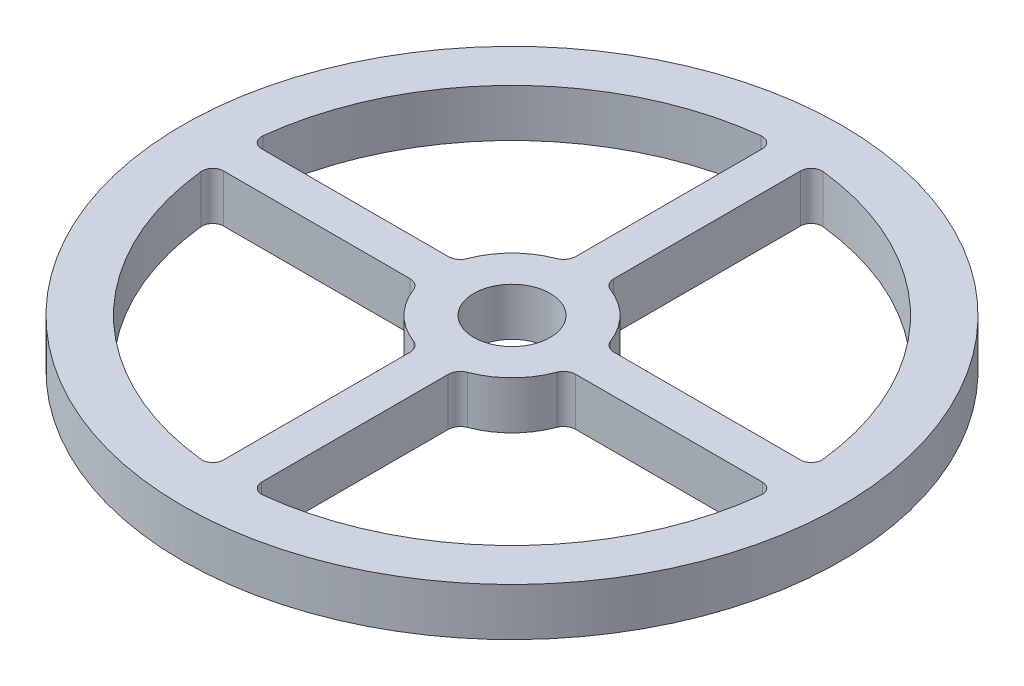
SolidWorks part; units mm, degrees
other "Markup1"
sketch "Sketch3" plane through (-32, 5, -32) normal (0, 1, 0) x (1, 0, 0)
sketch "Sketch4" plane through (-32, 5, -32) normal (0, 1, 0) x (1, 0, 0)
sketch "Sketch5" plane through (-32, 5, -32) normal (0, 1, 0) x (1, 0, 0)
sketch "Sketch6" plane through (-32, 5, -32) normal (0, 1, 0) x (1, 0, 0)
sketch "Sketch9" plane through (-34.5, 5, -34.5) normal (0, 1, 0) x (1, 0, 0)
ref_plane "Front Plane" through (0, 0, 0) normal (0, 0, 1) x (1, 0, 0)
ref_plane "Top Plane" through (0, 0, 0) normal (0, 1, 0) x (1, 0, 0)
ref_plane "Right Plane" through (0, 0, 0) normal (1, 0, 0) x (0, 0, -1)
sketch "Sketch1" plane through (0, 0, 0) normal (0, 1, 0) x (1, 0, 0)
  circle A0 centre (0, 0) radius 34.5
  circle A1 centre (0, 0) radius 4
  dimension "D1" = 69
  dimension "D2" = 8
extrude "Boss-Extrude1" add sketch "Sketch1" along normal blind 5
sketch "Sketch2" plane through (0, 5, 0) normal (0, 1, 0) x (1, 0, 0)
  line L2 (-4, 0) -> (-31.5, 0) construction
  line L3 (0, -4) -> (0, -31.5) construction
  circle A3 centre (0, 0) radius 34.5 construction
  arc A4 (-34.5, 0) -> (0, -34.5) centre (0, 0) ccw construction
  arc A5 (-4, 0) -> (0, -4) centre (0, 0) ccw construction
  circle A8 centre (0, 0) radius 4 construction
  arc A15 (-31.5, 0) -> (0, -31.5) centre (0, 0) ccw construction
  dimension "D1" = 3
sketch "Sketch8" plane through (0, 5, 0) normal (0, 1, 0) x (1, 0, 0)
  line L0 (-28.2013, -2) -> (-8.6981, -2)
  line L1 (-2, -8.646) -> (-2, -28.2087)
  line L2 (0, -4) -> (0, -31.5) construction
  line L3 (-4, 0) -> (-31.5, 0) construction
  line L4 (-2, -29.4587) -> (-3.1194, -28.2087) construction
  line L5 (-2, -28.2087) -> (-2, -30.1122) construction
  line L6 (-3.2424, -29.3213) -> (-2, -29.4587) construction
  line L7 (-29.4513, -2) -> (-28.2013, -3.126) construction
  line L8 (-28.2013, -2) -> (-32.0792, -2) construction
  line L9 (-2, -7.746) -> (-3.5301, -8.8637) construction
  line L10 (-2, -8.646) -> (-2, -7.668) construction
  line L11 (-2.8574, -7.4723) -> (-2, -7.746) construction
  line L12 (-8.6981, -2) -> (-7.2914, -2) construction
  line L13 (-7.4784, -2.8413) -> (-7.7981, -2) construction
  line L14 (-7.7981, -2) -> (-8.4859, -2.8754) construction
  line L15 (-2.8574, -7.4723) -> (-2.7871, -7.4988)
  arc A0 (-7.4784, -2.8413) -> (-2.7871, -7.4988) centre (0, 0) ccw
  arc A1 (-29.3204, -3.25) -> (-3.2424, -29.3213) centre (0, 0) ccw
  arc A2 (-4, 0) -> (0, -4) centre (0, 0) ccw construction
  arc A3 (-34.5, 0) -> (0, -34.5) centre (0, 0) ccw construction
  arc A4 (-3.2424, -29.3213) -> (-2, -28.2087) centre (-3.1194, -28.2087) ccw
  arc A5 (-28.2013, -2) -> (-29.3204, -3.25) centre (-28.2013, -3.126) ccw
  arc A6 (-2.8574, -7.4723) -> (-2, -8.646) centre (-3.2703, -8.6739) cw
  arc A7 (-8.6981, -2) -> (-7.4784, -2.8413) centre (-8.6981, -3.3047) cw
  point P21 (-2, -29.4587)
  point P22 (-28.2013, -2)
  point P23 (-29.4513, -2)
  point P24 (-30.2666, -1.0524)
  point P25 (-29.3204, -3.25)
  point P29 (-28.2013, -2)
  point P31 (-29.3204, -3.25)
  point P32 (-29.4513, -2)
  point P33 (-2, -8.646)
  point P34 (-2.8574, -7.4723)
  point P40 (-7.4784, -2.8413)
  point P42 (-2, -7.746)
  point P43 (-8.6981, -2)
  point P47 (0, 0)
  point P49 (-7.7981, -2)
  dimension "D3" = 4
  dimension "D4" = 5
  dimension "D9" = 1.1194
  dimension "D10" = 0.9
  dimension "D1" = 2
  dimension "D2" = 2
  dimension "D5" = 1.25
  dimension "D6" = 1.25
  dimension "D7" = 1.25
  dimension "D8" = 1.25
  dimension "D11" = 0.9
  dimension "D12" = 0.9
  dimension "D13" = 0.9
sketch "Sketch11" plane through (0, 5, 0) normal (0, 1, 0) x (1, 0, 0)
  line L0 (-29.0603, 13.1467) -> (-9.557, 13.1467)
  line L1 (-2.859, 6.5008) -> (-2.859, -13.0619)
  arc A0 (-8.3374, 12.3054) -> (-3.646, 7.6479) centre (-0.859, 15.1467) ccw
  arc A1 (-30.1794, 11.8967) -> (-4.1014, -14.1745) centre (-0.859, 15.1467) ccw
  arc A4 (-4.1014, -14.1745) -> (-2.859, -13.0619) centre (-3.9783, -13.0619) ccw
  arc A5 (-29.0603, 13.1467) -> (-30.1794, 11.8967) centre (-29.0603, 12.0208) ccw
  arc A6 (-3.7163, 7.6744) -> (-2.859, 6.5008) centre (-4.1292, 6.4728) cw
  arc A7 (-9.557, 13.1467) -> (-8.3374, 12.3054) centre (-9.557, 11.842) cw
  dimension "D9" = 1.1194
extrude "Cut-Extrude2" cut sketch "Sketch8" against normal through all contours A7 L0 A5 A1 A4 L1 A6 A0
sketch "Sketch12" plane through (0, 0, 0) normal (1, 0, 0) x (0, 0, -1)
  line L0 (0, 0) -> (0, 21.8148) construction
pattern_circular "CirPattern1" count 4 over 360 about axis through (0, 0, 0) along (0, 1, 0) of "Cut-Extrude2"
